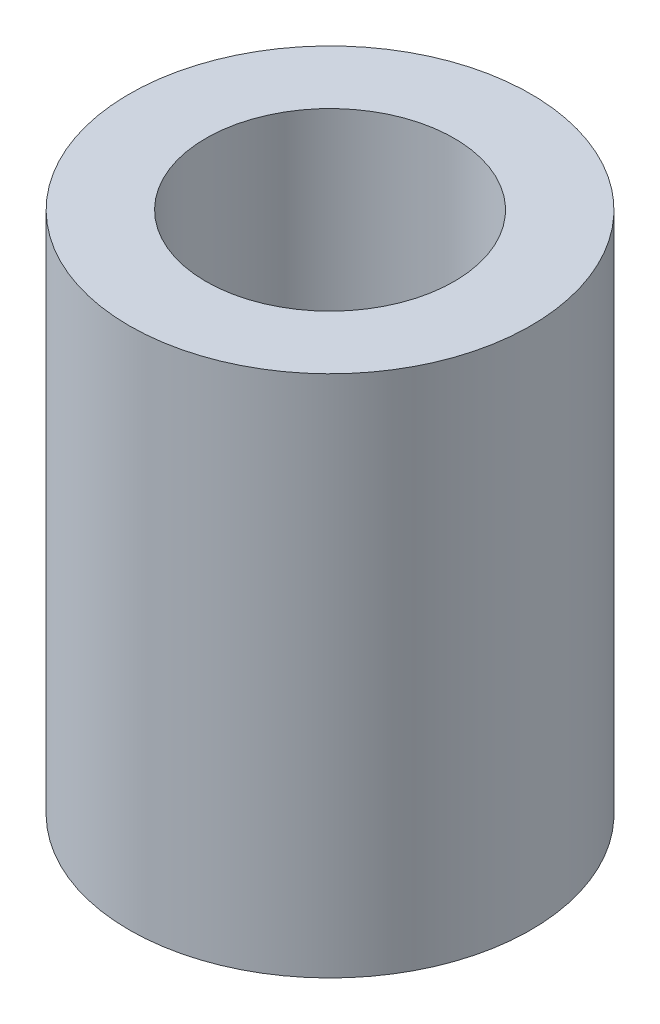
SolidWorks part; units mm, degrees
ref_plane "Front Plane" through (0, 0, 0) normal (0, 0, 1) x (1, 0, 0)
ref_plane "Top Plane" through (0, 0, 0) normal (0, 1, 0) x (1, 0, 0)
ref_plane "Right Plane" through (0, 0, 0) normal (1, 0, 0) x (0, 0, -1)
sketch "Sketch1" plane through (0, 0, 0) normal (0, 1, 0) x (1, 0, 0)
  circle A0 centre (0, 0) radius 3.2375
  circle A1 centre (0, 0) radius 5.2375
  dimension "D1" = 6.475
  dimension "D2" = 2
extrude "Boss-Extrude1" add sketch "Sketch1" along normal blind 13.65 contours A1 | A0
